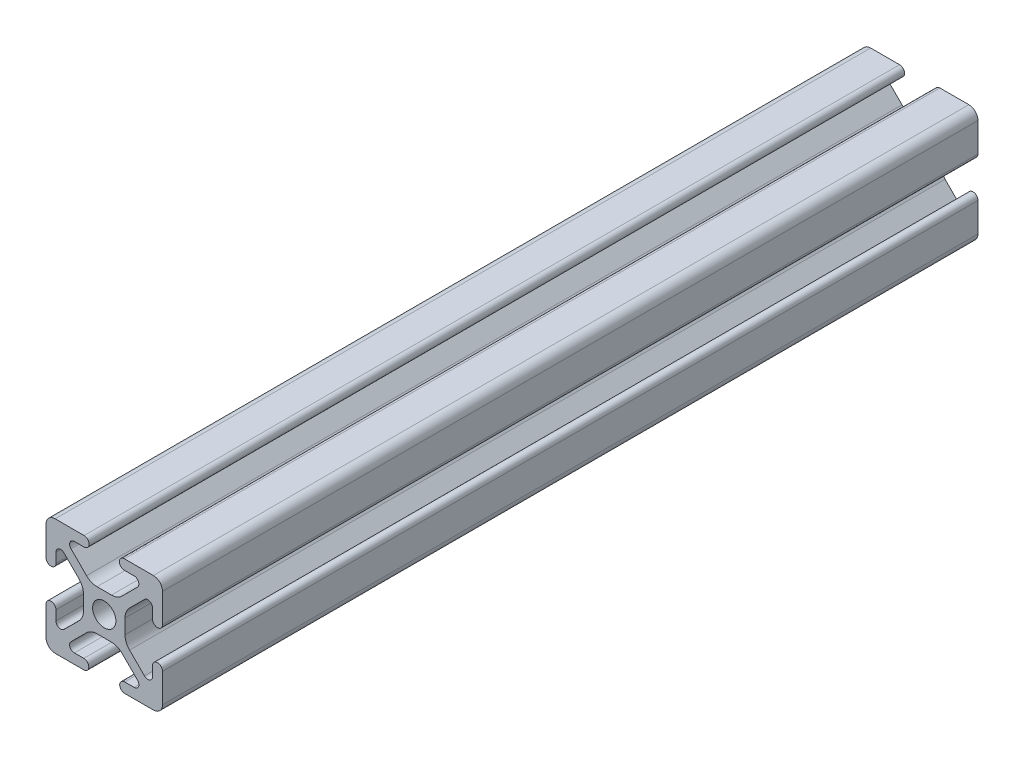
SolidWorks part; units mm, degrees
material "6005A-T61"
ref_plane "Front Plane" through (0, 0, 0) normal (0, 0, 1) x (1, 0, 0)
ref_plane "Top Plane" through (0, 0, 0) normal (0, 1, 0) x (1, 0, 0)
ref_plane "Right Plane" through (0, 0, 0) normal (1, 0, 0) x (0, 0, -1)
sketch "Sketch1" plane through (0, 0, 0) normal (0, 0, 1) x (1, 0, 0)
  line L0 (-8.6363, 7.1116) -> (-5.4322, 3.9121)
  line L1 (-4.455, 1.5554) -> (-4.455, -1.5554)
  line L2 (-5.4322, -3.9121) -> (-8.6363, -7.1116)
  line L3 (-10.36, -6.3969) -> (-10.36, -4.32)
  line L4 (-12.5, -4.32) -> (-12.5, -8.6518)
  line L5 (-12.5, -8.6518) -> (-12.5, -10.5371)
  line L6 (-10.5371, -12.5) -> (-8.4416, -12.5)
  line L7 (-8.4416, -12.5) -> (-4.3879, -12.5)
  line L8 (-4.3879, -10.36) -> (-6.42, -10.36)
  line L9 (-7.1337, -8.6353) -> (-3.7953, -5.3018)
  line L10 (-1.5554, -4.375) -> (1.5554, -4.375)
  line L11 (10.36, 4.32) -> (10.36, 6.3969)
  line L12 (12.5, 7.9913) -> (12.5, 4.32)
  line L13 (12.5, 10.5371) -> (12.5, 7.9913)
  line L14 (4.32, 12.5) -> (10.5371, 12.5)
  line L16 (6.42, 10.36) -> (4.32, 10.36)
  line L17 (3.7953, 5.3018) -> (7.1337, 8.6353)
  line L18 (7.1337, -8.6353) -> (3.7953, -5.3018)
  line L19 (4.3879, -10.36) -> (6.42, -10.36)
  line L20 (8.4416, -12.5) -> (4.3879, -12.5)
  line L21 (10.5371, -12.5) -> (8.4416, -12.5)
  line L22 (12.5, -8.6518) -> (12.5, -10.5371)
  line L23 (12.5, -4.32) -> (12.5, -8.6518)
  line L24 (10.36, -6.3969) -> (10.36, -4.32)
  line L25 (5.4322, -3.9121) -> (8.6363, -7.1116)
  line L26 (4.455, 1.5554) -> (4.455, -1.5554)
  line L27 (8.6363, 7.1116) -> (5.4322, 3.9121)
  line L28 (1.5554, 4.375) -> (-1.5554, 4.375)
  line L29 (-3.7953, 5.3018) -> (-7.1337, 8.6353)
  line L30 (-6.42, 10.36) -> (-4.32, 10.36)
  line L32 (-4.32, 12.5) -> (-10.5371, 12.5)
  line L33 (-12.5, 10.5371) -> (-12.5, 7.9913)
  line L34 (-12.5, 7.9913) -> (-12.5, 4.32)
  line L35 (-10.36, 4.32) -> (-10.36, 6.3969)
  line L36 (-15.7693, 0) -> (12.5, 0) construction
  line L37 (0, 13.9334) -> (0, -12.3541) construction
  circle A0 centre (0, 0) radius 2.5
  arc A1 (-8.6363, 7.1116) -> (-10.36, 6.3969) centre (-9.35, 6.3969) ccw
  arc A2 (-4.455, 1.5554) -> (-5.4322, 3.9121) centre (-7.7855, 1.5554) ccw
  arc A3 (-5.4322, -3.9121) -> (-4.455, -1.5554) centre (-7.7855, -1.5554) ccw
  arc A4 (-10.36, -6.3969) -> (-8.6363, -7.1116) centre (-9.35, -6.3969) ccw
  arc A5 (-10.36, -4.32) -> (-12.5, -4.32) centre (-11.43, -4.32) ccw
  arc A6 (-12.5, -10.5371) -> (-10.5371, -12.5) centre (-10.5371, -10.5371) ccw
  arc A7 (-4.3879, -12.5) -> (-4.3879, -10.36) centre (-4.3879, -11.43) ccw
  arc A8 (-7.1337, -8.6353) -> (-6.42, -10.36) centre (-6.42, -9.35) ccw
  arc A9 (-1.5554, -4.375) -> (-3.7953, -5.3018) centre (-1.5554, -7.545) ccw
  arc A10 (12.5, 4.32) -> (10.36, 4.32) centre (11.43, 4.32) cw
  arc A11 (10.5371, 12.5) -> (12.5, 10.5371) centre (10.5371, 10.5371) cw
  arc A12 (4.32, 10.36) -> (4.32, 12.5) centre (4.32, 11.43) cw
  arc A13 (6.42, 10.36) -> (7.1337, 8.6353) centre (6.42, 9.35) cw
  arc A14 (3.7953, 5.3018) -> (1.5554, 4.375) centre (1.5554, 7.545) cw
  arc A15 (1.5554, -4.375) -> (3.7953, -5.3018) centre (1.5554, -7.545) cw
  arc A16 (7.1337, -8.6353) -> (6.42, -10.36) centre (6.42, -9.35) cw
  arc A17 (4.3879, -12.5) -> (4.3879, -10.36) centre (4.3879, -11.43) cw
  arc A18 (12.5, -10.5371) -> (10.5371, -12.5) centre (10.5371, -10.5371) cw
  arc A19 (10.36, -4.32) -> (12.5, -4.32) centre (11.43, -4.32) cw
  arc A20 (10.36, -6.3969) -> (8.6363, -7.1116) centre (9.35, -6.3969) cw
  arc A21 (5.4322, -3.9121) -> (4.455, -1.5554) centre (7.7855, -1.5554) cw
  arc A22 (4.455, 1.5554) -> (5.4322, 3.9121) centre (7.7855, 1.5554) cw
  arc A23 (8.6363, 7.1116) -> (10.36, 6.3969) centre (9.35, 6.3969) cw
  arc A24 (-3.7953, 5.3018) -> (-1.5554, 4.375) centre (-1.5554, 7.545) ccw
  arc A25 (-6.42, 10.36) -> (-7.1337, 8.6353) centre (-6.42, 9.35) ccw
  arc A26 (-4.32, 10.36) -> (-4.32, 12.5) centre (-4.32, 11.43) ccw
  arc A27 (-10.5371, 12.5) -> (-12.5, 10.5371) centre (-10.5371, 10.5371) ccw
  arc A28 (-12.5, 4.32) -> (-10.36, 4.32) centre (-11.43, 4.32) ccw
  dimension "D4" = 14.86
  dimension "D5" = 2.14
  dimension "D6" = 6.5
  dimension "D7" = 8.75
  dimension "D8" = 1.01
  dimension "D9" = 3.17
  dimension "D14" = 5
  dimension "D1" = 25
  dimension "D2" = 8.91
  dimension "D3" = 12.5
  dimension "D12" = 2.14
extrude "Extrude1" add sketch "Sketch1" against normal blind 175
sketch "Sketch2" plane through (4.455, 0, 0) normal (1, 0, 0) x (0, 0, -1)
  circle A0 centre (14.0555, 0) radius 0.4941
extrude "Cut-Extrude1" cut sketch "Sketch2" against normal through all
